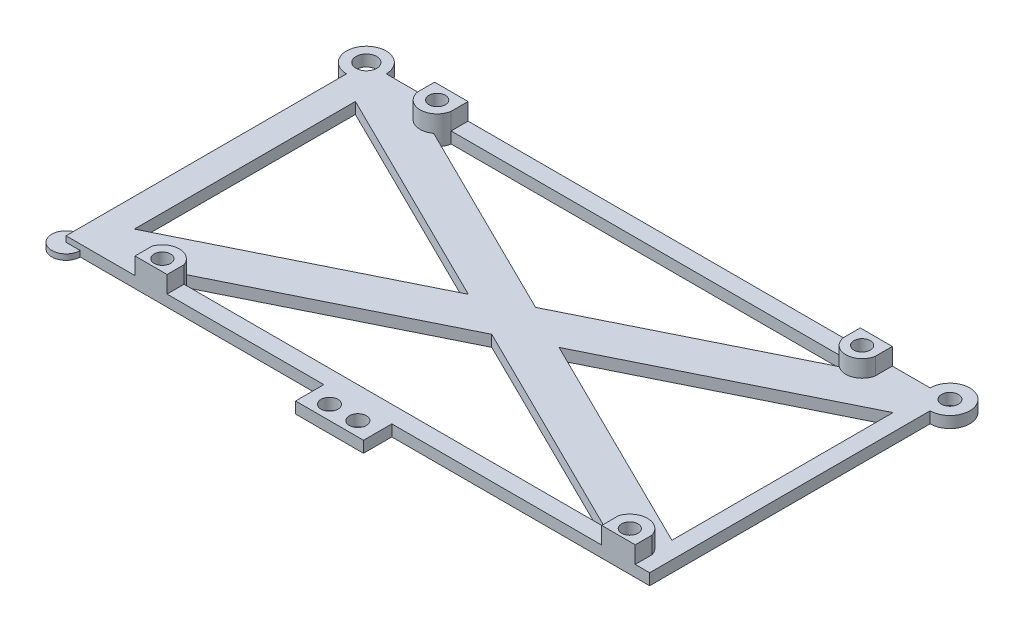
SolidWorks part; units mm, degrees
ref_plane "前视基准面" through (0, 0, 0) normal (0, 0, 1) x (1, 0, 0)
ref_plane "上视基准面" through (0, 0, 0) normal (0, 1, 0) x (1, 0, 0)
ref_plane "右视基准面" through (0, 0, 0) normal (1, 0, 0) x (0, 0, -1)
sketch "Sketch1" plane through (0, 0, 0) normal (0, 1, 0) x (1, 0, 0)
  line L0 (40.3284, 24) -> (40.3284, 26.5)
  line L1 (-52.5, -26.5) -> (-7, -26.5)
  line L2 (-52.5, -26.5) -> (-52.5, 23)
  line L3 (-49, 26.5) -> (47, 26.5)
  line L5 (-52.5, -26.5) -> (52.5, 26.5) construction
  line L6 (-52.5, 26.5) -> (52.5, -26.5) construction
  line L7 (-37.5, 25.45) -> (-37.5, 24)
  line L8 (-37.5, 24) -> (-36.05, 24)
  line L9 (-49, 26.5) -> (47, 26.5)
  line L10 (47.5, 22.3417) -> (50.5, 22.3417)
  line L11 (38.55, -23.5) -> (40.3284, -23.5)
  line L12 (5, -26.5) -> (47.3979, -26.5)
  line L13 (-49, 26.5) -> (-37.5, 26.5)
  line L14 (-1, -31.5) -> (-7, -31.5)
  line L15 (-1, -31.5) -> (5, -31.5)
  line L16 (5, -31.5) -> (5, -26.5)
  line L17 (-7, -31.5) -> (-7, -26.5)
  line L18 (36.1574, -21.8172) -> (39.5589, -23.5)
  line L19 (50.5, 23) -> (50.5, -26.5)
  line L20 (-52.5, 0) -> (-49.5, 0)
  line L21 (-40.3284, -23.5) -> (-40.3284, -26.5)
  line L22 (-34.6716, -23.5) -> (-34.6716, -26.5)
  line L23 (-40.458, 23.5) -> (-40.458, 26.5)
  line L24 (-34.542, 23.5) -> (-34.542, 26.5)
  line L25 (47.5, -19.6963) -> (47.5, -22.6292)
  line L26 (-47.5, -19.4515) -> (-47.5, 19.6963)
  line L27 (40.3284, -23.5) -> (42.042, -23.5)
  line L28 (47.5, -19.6963) -> (47.5, 19.5842)
  line L29 (-3.9706, -1.9644) -> (47.5, 23.5) construction
  line L30 (-47.5, 23.5) -> (47.5, -23.5) construction
  line L31 (36.1574, -21.8172) -> (0.121, -3.9886)
  line L32 (-34.542, 23.5) -> (34.6716, 23.5)
  line L33 (46.3611, 23.5) -> (46.5566, 23.5)
  line L34 (-34.6716, -23.5) -> (34.6716, -23.5)
  line L35 (47.5, -19.5712) -> (8.0621, -0.0599)
  line L36 (46.3611, 23.5) -> (46.5566, 23.5) construction
  line L37 (47.5, 23.5) -> (47.5, 22.3417) construction
  line L38 (34.6716, 23.5) -> (34.6716, 26.5)
  line L39 (-1, 0) -> (0, 0)
  line L40 (-45.9385, 26.6562) -> (-46.0158, 26.5)
  line L41 (0, 0) -> (-0.0702, -0.0585)
  line L42 (-1, 0) -> (0, 0)
  line L43 (45.9385, -26.6562) -> (45.6227, -26.5)
  line L44 (49.0615, -20.3438) -> (-49.0615, 20.3438) construction
  line L45 (-45.9385, 26.6562) -> (37.0988, -21.5269) construction
  line L46 (47.5, 19.4515) -> (8.0621, -0.0599)
  line L47 (49.1091, 20.2476) -> (49.052, 20.3629)
  line L48 (41.8775, -24.5) -> (42.2225, -24.5)
  line L49 (42.042, -16.8709) -> (42.042, -17.4331)
  line L50 (49.1091, 20.2476) -> (-47.5, -19.5842) construction
  line L51 (-45.4579, -26.5) -> (45.4579, 26.5) construction
  line L52 (34.6716, -23.5) -> (38.55, -23.5)
  line L53 (42.042, -20.7997) -> (42.042, -21.2212)
  line L54 (-40.4991, 23.5) -> (-40.458, 23.5)
  line L55 (-45.6227, 26.5) -> (-45.9385, 26.6562)
  line L56 (-37.6556, 22.5584) -> (-38.5516, 23.0017)
  line L57 (-0.121, 3.9886) -> (-35.7073, 21.5945)
  line L58 (-3.766, 2.1853) -> (-4.4518, 1.846)
  line L59 (-8.0621, 0.0599) -> (-47.5, 19.5712)
  line L60 (-8.0621, 0.0599) -> (-47.5, -19.4515)
  line L61 (-3.6455, -2.1252) -> (-4.3314, -1.7858)
  line L62 (4.3314, 1.7858) -> (3.6455, 2.1252)
  line L63 (0.121, -3.9886) -> (-36.0404, -21.879)
  line L64 (35.7398, 21.7303) -> (-0.121, 3.9886)
  line L65 (42.042, -24.3952) -> (42.042, -24.5)
  line L66 (46.0158, -26.5) -> (45.9385, -26.6562)
  line L67 (34.6716, -23.5) -> (34.6716, -13.2245)
  line L68 (40.3284, -23.5) -> (40.3284, -16.0232)
  line L69 (40.2803, -23.373) -> (45.9385, -26.6562) construction
  line L70 (38.8611, 23.5) -> (39.3169, 23.5)
  line L71 (40.3284, 23.5) -> (40.3284, 24)
  line L72 (42.042, -23.5) -> (42.042, -26.5)
  line L73 (47.5, -26.5) -> (50.5, -26.5)
  line L74 (47.958, -23.5) -> (47.958, -26.5)
  line L75 (47.3979, -26.5) -> (47.5, -26.5)
  line L76 (47.5, -26.5) -> (47.5028, -26.497)
  circle A0 centre (-37.5, 24) radius 1.45
  circle A1 centre (-37.5, -24.5) radius 1.45
  arc A3 (42.042, -23.5) -> (47.958, -23.5) centre (45, -24.5) cw
  circle A4 centre (-3.5, -29) radius 1.5
  circle A5 centre (1.5, -29) radius 1.5
  arc A6 (-49, 26.5) -> (-52.5, 23) centre (-52.5, 26.5) ccw
  arc A7 (52.5, 23.6277) -> (47.0107, 26.2264) centre (50.5, 26.5) ccw
  circle A8 centre (-52.5, 26.5) radius 1.8234
  circle A9 centre (50.5, 26.5) radius 1.5
  arc A10 (-40.458, 23.5) -> (-34.542, 23.5) centre (-37.5, 24) ccw
  arc A12 (-34.6716, -23.5) -> (-40.3284, -23.5) centre (-37.5, -24.5) ccw
  arc A13 (40.3284, -23.5) -> (40.2803, -23.373) centre (37.5, -24.5) ccw
  circle A14 centre (45, -24.5) radius 1.45
  arc A15 (47.9996, 24.051) -> (47.9916, 24.2243) centre (45, 24) ccw
  arc A16 (47.8869, 24.1715) -> (47.9996, 24.051) centre (50.5, 26.5) ccw
  arc A17 (50.5, 23) -> (52.5, 23.6277) centre (50.5, 26.5) ccw
  arc A18 (-52.5, 23) -> (-49, 26.5) centre (-52.5, 26.5) ccw
  arc A19 (47, 26.5) -> (50.5, 23) centre (50.5, 26.5) ccw
  arc A20 (45.6972, -26.5) -> (45.948, -26.6371) centre (47.5, -23.5) ccw
  arc A22 (41.8837, -24.3034) -> (41.8775, -24.5) centre (45, -24.5) ccw
  circle A24 centre (37.5, 24) radius 1.45
  arc A25 (34.6716, 23.5) -> (40.3303, 23.5108) centre (37.5, 24) ccw
  arc A26 (-45.6972, 26.5) -> (-45.948, 26.6371) centre (-47.5, 23.5) ccw
  arc A27 (50.4098, -25.445) -> (50.5, -25.3028) centre (47.5, -23.5) ccw
  arc A29 (46.3082, 23.3746) -> (46.3611, 23.5) centre (45, 24) ccw
  point P0 (0, 0)
  point P39 (0, 0)
extrude "Boss-Extrude1" add sketch "Sketch1" along normal blind 2
sketch "Sketch2" plane through (0, 0, 0) normal (0, 1, 0) x (1, 0, 0)
  line L0 (-40.458, 23.5) -> (-40.458, 26.5) construction
  line L1 (-49, 26.5) -> (47, 26.5) construction
  line L2 (-34.542, 23.5) -> (-34.542, 26.5) construction
  line L3 (-40.458, 23.5) -> (-40.458, 26.5)
  line L4 (-49, 26.5) -> (47, 26.5)
  line L5 (-34.542, 23.5) -> (-34.542, 26.5)
  line L6 (-40.3284, -23.5) -> (-40.3284, -26.5) construction
  line L7 (-52.5, -26.5) -> (-7, -26.5) construction
  line L8 (-34.6716, -23.5) -> (-34.6716, -26.5) construction
  line L9 (42.042, -23.5) -> (42.042, -26.5) construction
  line L10 (5, -26.5) -> (47.3979, -26.5) construction
  line L11 (47.958, -23.5) -> (47.958, -26.5) construction
  line L12 (34.6716, 23.5) -> (34.6716, 26.5) construction
  line L13 (40.3284, 24) -> (40.3284, 26.5) construction
  line L14 (40.3284, 23.5) -> (40.3284, 24) construction
  line L15 (-40.3284, -23.5) -> (-40.3284, -26.5)
  line L16 (-52.5, -26.5) -> (-7, -26.5)
  line L17 (-34.6716, -23.5) -> (-34.6716, -26.5)
  line L18 (42.042, -23.5) -> (42.042, -26.5)
  line L19 (5, -26.5) -> (47.3979, -26.5)
  line L20 (47.958, -23.5) -> (47.958, -26.5)
  line L21 (34.6716, 23.5) -> (34.6716, 26.5)
  line L22 (40.3284, 24) -> (40.3284, 26.5)
  line L23 (40.3284, 23.5) -> (40.3284, 24)
  line L24 (47.958, -26.5636) -> (47.958, -26.5)
  line L25 (47.3979, -26.5) -> (47.958, -26.5)
  circle A0 centre (-37.5, 24) radius 1.45 construction
  arc A1 (-40.458, 23.5) -> (-34.542, 23.5) centre (-37.5, 24) ccw construction
  circle A2 centre (-37.5, 24) radius 1.45
  arc A3 (-40.458, 23.5) -> (-34.542, 23.5) centre (-37.5, 24) ccw
  arc A4 (-34.6716, -23.5) -> (-40.3284, -23.5) centre (-37.5, -24.5) ccw construction
  circle A5 centre (-37.5, -24.5) radius 1.45 construction
  circle A6 centre (45, -24.5) radius 1.45 construction
  arc A7 (47.958, -23.5) -> (42.042, -23.5) centre (45, -24.5) ccw construction
  circle A8 centre (37.5, 24) radius 1.45 construction
  arc A9 (34.6716, 23.5) -> (40.3303, 23.5108) centre (37.5, 24) ccw construction
  arc A10 (-34.6716, -23.5) -> (-40.3284, -23.5) centre (-37.5, -24.5) ccw
  circle A11 centre (-37.5, -24.5) radius 1.45
  circle A12 centre (45, -24.5) radius 1.45
  arc A13 (47.958, -23.5) -> (42.042, -23.5) centre (45, -24.5) ccw
  circle A14 centre (37.5, 24) radius 1.45
  arc A15 (34.6716, 23.5) -> (40.3303, 23.5108) centre (37.5, 24) ccw
extrude "Boss-Extrude2" add sketch "Sketch2" along normal blind 5 contours L17 A10 L15 L16 A11 | L3 A3 L5 L4 A2 | L20 A13 L18 L19 L25 A12 | L21 A15 L23 L22 L4 A14
sketch "Sketch3" plane through (0, 0, 0) normal (0, 1, 0) x (1, 0, 0)
  circle A0 centre (-52.5, -26.5) radius 2.5
  arc A1 (-49, 26.5) -> (-52.5, 23) centre (-52.5, 26.5) ccw construction
  arc A2 (-49, 26.5) -> (-52.5, 23) centre (-52.5, 26.5) ccw
extrude "Boss-Extrude3" add sketch "Sketch3" along normal blind 1 contours A0
